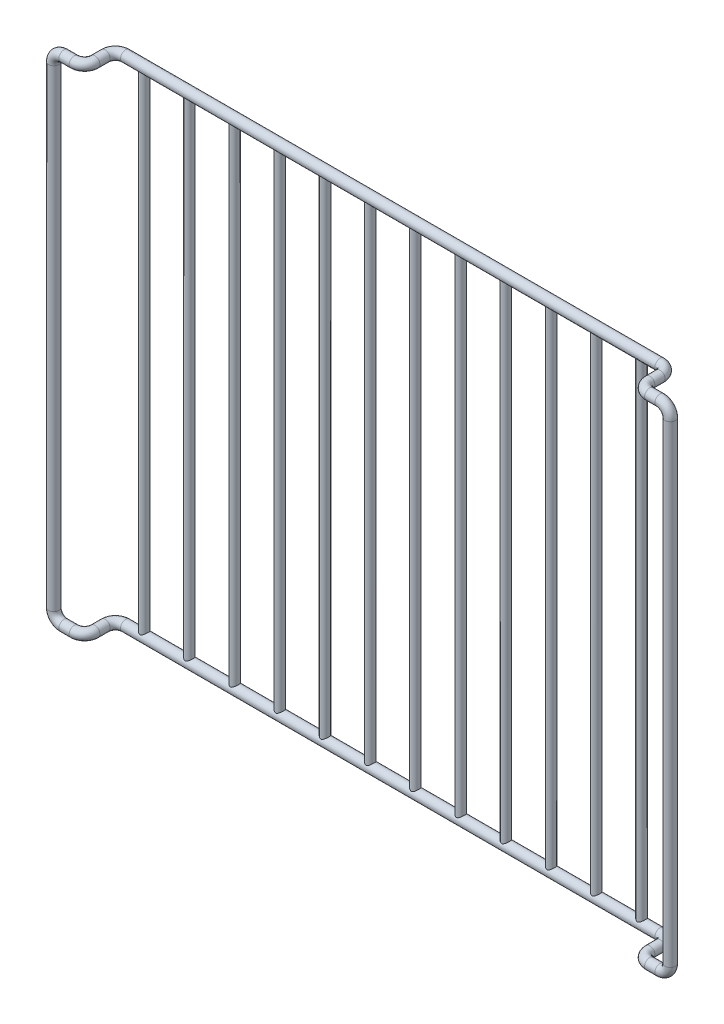
SolidWorks part; units mm, degrees
ref_plane "Front Plane" through (0, 0, 0) normal (0, 0, 1) x (1, 0, 0)
ref_plane "Top Plane" through (0, 0, 0) normal (0, 1, 0) x (1, 0, 0)
ref_plane "Right Plane" through (0, 0, 0) normal (1, 0, 0) x (0, 0, -1)
sketch3d "3DSketch1"
  line L0 (0, 0, 0) -> (130, 0, 0)
  line L1 (135, 0, 5) -> (135, 0, 10)
  line L2 (140, 0, 15) -> (145, 0, 15)
  line L3 (150, -5, 15) -> (150, -235, 15)
  line L4 (145, -240, 15) -> (140, -240, 15)
  line L5 (135, -240, 10) -> (135, -240, 5)
  line L6 (130, -240, 0) -> (0, -240, 0)
  arc A0 (140, 0, 15) -> (135, 0, 10) centre (140, 0, 10) ccw
  arc A1 (140, -240, 15) -> (135, -240, 10) centre (140, -240, 10) ccw
  arc A2 (150, -235, 15) -> (145, -240, 15) centre (145, -235, 15) ccw
  arc A3 (135, -240, 5) -> (130, -240, 0) centre (130, -240, 5) ccw
  arc A4 (145, 0, 15) -> (150, -5, 15) centre (145, -5, 15) ccw
  arc A5 (135, 0, 5) -> (130, 0, 0) centre (130, 0, 5) ccw
  point P9 (0, 0, 0)
  point P10 (-0.5781, -240.6849, 0.0268)
  point P11 (135, -241.2455, 0.0518)
  point P14 (135, 0, 15)
  point P15 (140, -5, 10)
  point P18 (135, -240, 15)
  point P19 (140, -245, 10)
  point P22 (150, -240, 15)
  point P23 (145, -235, 10)
  point P26 (135, -240, 0)
  point P27 (130, -235, 5)
  point P30 (150, 0, 15)
  point P31 (145, -5, 10)
  point P34 (135, 0, 0)
  point P35 (130, 5, 5)
  dimension "D8" = 5
  dimension "D9" = 5
  dimension "D10" = 5
  dimension "D1" = 135
  dimension "D2" = 15
  dimension "D3" = 15
  dimension "D4" = 240
  dimension "D5" = 15
  dimension "D6" = 15
  dimension "D7" = 135
sketch "Sketch1" plane through (0, 0, 0) normal (1, 0, 0) x (0, 0, -1)
  circle A0 centre (0, 0) radius 2.5
  dimension "D1" = 5
sweep "Sweep1" add profiles "Sketch1" path "3DSketch1"
sketch "Sketch3" plane through (0, 0, 0) normal (0, 1, 0) x (1, 0, 0)
  line L0 (0, -2.5) -> (130, -2.5) construction
  line L1 (130, 2.5) -> (0, 2.5) construction
  line L2 (0, 2.5) -> (0, -2.5) construction
  line L3 (0, -2.5) -> (130, -2.5)
  line L4 (130, 2.5) -> (0, 2.5)
  line L5 (0, 2.5) -> (0, -2.5)
  circle A0 centre (11, 0) radius 2
  point P6 (0, 0)
  dimension "D1" = 4
  dimension "D2" = 11
extrude "Boss-Extrude1" add sketch "Sketch3" against normal up to surface (238.5 mm away) contours A0
pattern_linear "LPattern1" count 6 spacing 22 along (1, 0, 0) of "Boss-Extrude1"
mirror "Mirror1" about plane through (0, -240, 0) normal (-1, 0, 0) of bodies 103
